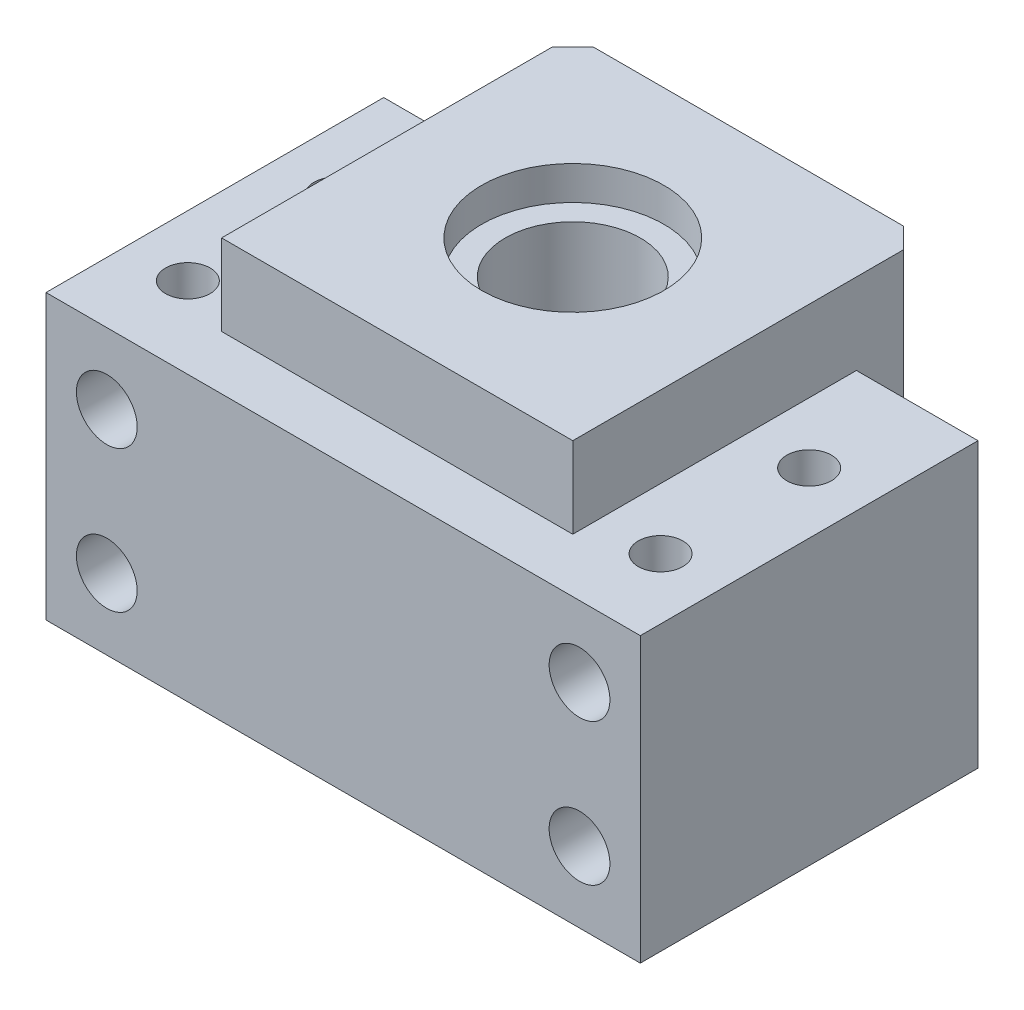
SolidWorks part; units mm, degrees
material "合金钢"
ref_plane "前视基准面" through (0, 0, 0) normal (0, 0, 1) x (1, 0, 0)
ref_plane "上视基准面" through (0, 0, 0) normal (0, 1, 0) x (1, 0, 0)
ref_plane "右视基准面" through (0, 0, 0) normal (1, 0, 0) x (0, 0, -1)
sketch "草图1" plane through (0, 0, 0) normal (0, 1, 0) x (1, 0, 0)
  line L0 (0, 25) -> (0, -25) construction
  line L1 (-44, 25) -> (44, 25)
  line L2 (-44, 25) -> (-44, -25)
  line L3 (-44, -25) -> (44, -25)
  line L4 (44, 25) -> (44, -25)
  circle A0 centre (35, 9) radius 3.3
  circle A1 centre (35, -13) radius 3.3
  circle A2 centre (-35, -13) radius 3.3
  circle A3 centre (-35, 9) radius 3.3
  point P4 (0, 25)
  point P6 (44, 0)
  dimension "D3" = 6.6
  dimension "D1" = 88
  dimension "D2" = 50
  dimension "D4" = 34
  dimension "D5" = 22
  dimension "D6" = 70
extrude "凸台-拉伸1" add sketch "草图1" along normal blind 42
sketch "草图2" plane through (0, 0, 0) normal (0, 1, 0) x (1, 0, 0)
  line L0 (-44, -25) -> (44, -25) construction
  line L1 (-26, 35) -> (26, 35)
  line L2 (-26, 35) -> (-26, -17)
  line L3 (-26, -17) -> (26, -17)
  line L4 (26, 35) -> (26, -17)
  point P6 (0, 35)
  dimension "D1" = 60
  dimension "D2" = 52
extrude "凸台-拉伸2" add sketch "草图2" along normal blind 54
sketch "草图3" plane through (0, 0, -25) normal (0, 0, -1) x (-1, 0, 0)
  line L0 (0, 54) -> (0, 0) construction
  line L1 (-26, 54) -> (26, 54) construction
  line L3 (-44, 42) -> (-26, 42) construction
  line L4 (-44, 0) -> (-26, 0) construction
  circle A0 centre (35, 31.5) radius 7
  circle A1 centre (35, 10.5) radius 7
  circle A2 centre (-35, 10.5) radius 7
  circle A3 centre (-35, 31.5) radius 7
  dimension "D1" = 14
  dimension "D2" = 70
  dimension "D3" = 10.5
  dimension "D4" = 10.5
extrude "切除-拉伸1" cut sketch "草图3" against normal blind 12
sketch "草图4" plane through (0, 0, -13) normal (0, 0, -1) x (-1, 0, 0)
  line L0 (0, 0) -> (0, 54) construction
  line L1 (-26, 0) -> (26, 0) construction
  line L2 (-26, 54) -> (26, 54) construction
  circle A0 centre (35, 31.5) radius 4.5
  circle A1 centre (35, 10.5) radius 4.5
  circle A2 centre (-35, 10.5) radius 4.5
  circle A3 centre (-35, 31.5) radius 4.5
  dimension "D1" = 9
extrude "切除-拉伸2" cut sketch "草图4" against normal through all
sketch "草图5" plane through (0, 0, 0) normal (0, 1, 0) x (1, 0, 0)
  line L0 (-44, -25) -> (44, -25) construction
  circle A0 centre (0, 9) radius 10
  dimension "D2" = 20
  dimension "D1" = 34
extrude "切除-拉伸3" cut sketch "草图5" along normal through all
sketch "草图6" plane through (0, 54, 0) normal (0, 1, 0) x (1, 0, 0)
  circle A0 centre (0, 9) radius 13.5
  dimension "D1" = 27
extrude "切除-拉伸4" cut sketch "草图6" against normal blind 5
chamfer "倒角1" distance 3 angle 45 2 edges at (26, 27, -35) (-26, 27, -35)
